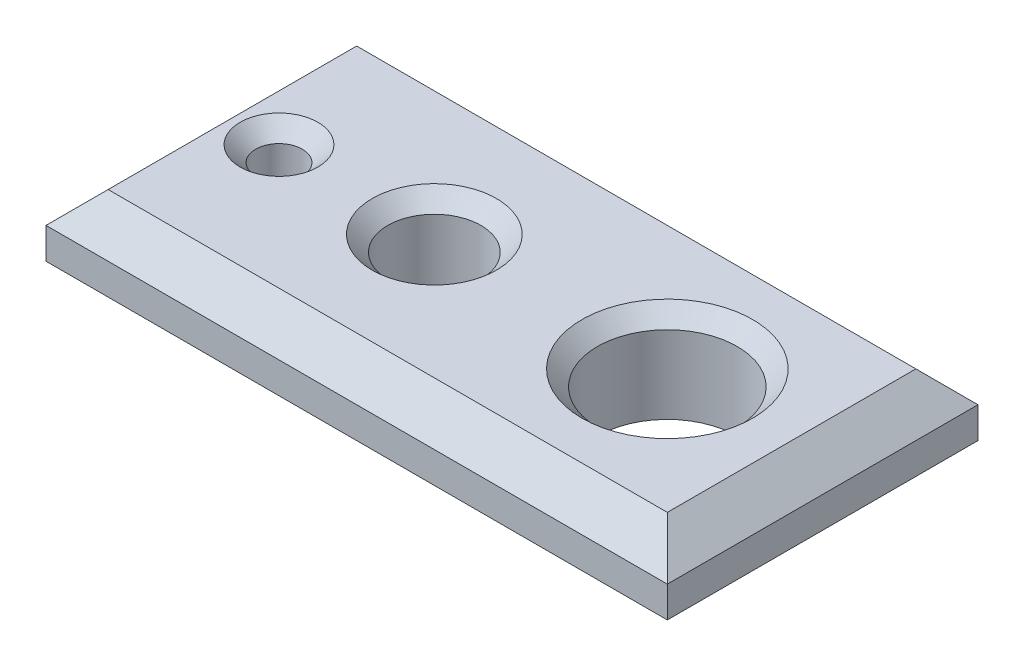
SolidWorks part; units mm, degrees
ref_plane "前基準面" through (0, 0, 0) normal (0, 0, 1) x (1, 0, 0)
ref_plane "上基準面" through (0, 0, 0) normal (0, 1, 0) x (1, 0, 0)
ref_plane "右基準面" through (0, 0, 0) normal (1, 0, 0) x (0, 0, -1)
ref_plane "平面1"
sketch "草圖1" plane through (0, 0, 0) normal (0, 1, 0) x (-1, 0, 0)
  line L0 (0, 0) -> (-200, 0)
  line L1 (-200, 0) -> (-200, -100)
  line L2 (-200, -100) -> (0, -100)
  line L3 (0, -100) -> (0, 0)
  dimension "D1" = 200
  dimension "D2" = 100
extrude "擠出1" add sketch "草圖1" along normal blind 30
sketch "草圖2" plane through (0, 30, 0) normal (0, 1, 0) x (-1, 0, 0)
  circle A0 centre (-25, -50) radius 7.5
  circle A1 centre (-75, -50) radius 15
  circle A2 centre (-150, -50) radius 22.5
  dimension "D1" = 45
  dimension "D2" = 30
  dimension "D3" = 15
  dimension "D4" = 50
  dimension "D5" = 75
extrude "擠出2" cut sketch "草圖2" against normal blind 30
chamfer "倒角1" distance 5 distance2 5 3 edges at (25, 30, -42.5) (75, 30, -35) (150, 30, -27.5)
chamfer "倒角2" distance 10 distance2 10 4 edges at (200, 30, -50) (100, 30, -100) (0, 30, -50) (100, 30, 0)
chamfer "倒角3" distance 10 distance2 10 4 edges at (100, 0, 0) (200, 0, -50) (100, 0, -100) (0, 0, -50)
